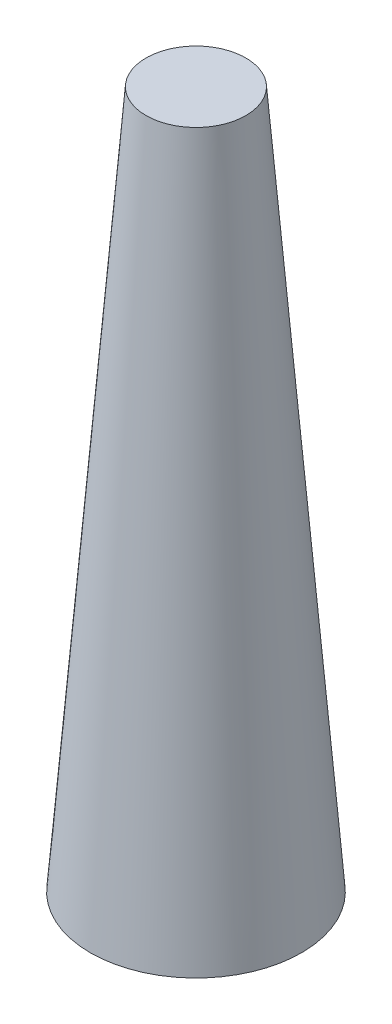
SolidWorks part; units mm, degrees
material "ABS"
ref_plane "Front Plane" through (0, 0, 0) normal (0, 0, 1) x (1, 0, 0)
ref_plane "Top Plane" through (0, 0, 0) normal (0, 1, 0) x (1, 0, 0)
ref_plane "Right Plane" through (0, 0, 0) normal (1, 0, 0) x (0, 0, -1)
sketch "Sketch1" plane through (0, 0, 0) normal (0, 1, 0) x (1, 0, 0)
  circle A0 centre (0, 0) radius 2.54
  dimension "D1" = 5.08
ref_plane "Plane1" through (0, 16.764, 0) normal (0, 1, 0) x (1, 0, 0)
sketch "Sketch2" plane through (0, 16.764, 0) normal (0, 1, 0) x (1, 0, 0)
  circle A0 centre (0, 0) radius 1.2001
  dimension "D1" = 2.4003
loft "Loft1" add profiles "Sketch2", "Sketch1"
